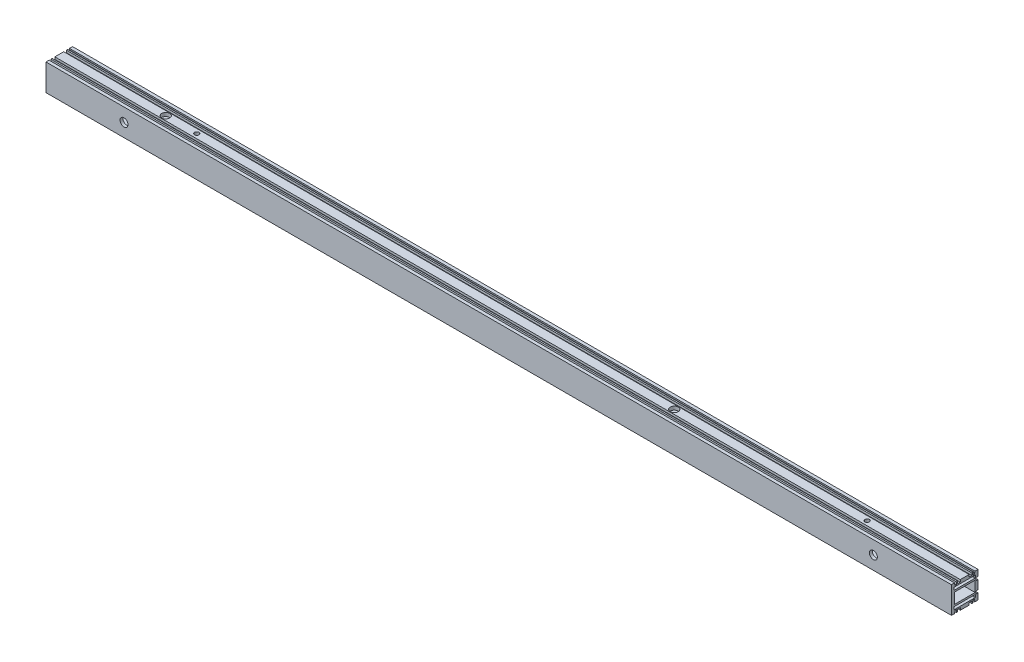
SolidWorks part; units mm, degrees
ref_plane "前视基准面" through (0, 0, 0) normal (0, 0, 1) x (1, 0, 0)
ref_plane "上视基准面" through (0, 0, 0) normal (0, 1, 0) x (1, 0, 0)
ref_plane "右视基准面" through (0, 0, 0) normal (1, 0, 0) x (0, 0, -1)
sketch "草图1" plane through (0, 0, 0) normal (1, 0, 0) x (0, 0, -1)
  line L0 (-15, 15) -> (15, -15) construction
  line L1 (-15, 15) -> (-11.5, 15)
  line L2 (-15, 15) -> (-15, -15)
  line L3 (-15, -15) -> (-11.5, -15)
  line L4 (15, 15) -> (15, 8)
  line L5 (15, 15) -> (-15, -15) construction
  line L6 (-11.5, 15) -> (-11.5, 13.5)
  line L7 (-11.5, 13.5) -> (-11, 13.5)
  line L8 (-11, 13.5) -> (-11, 12)
  line L9 (-11, 12) -> (-9.5, 12)
  line L10 (-9.5, 12) -> (-9.5, 15)
  line L11 (-9.5, 15) -> (-8, 15)
  line L12 (-8, 15) -> (-8, 12.5)
  line L13 (-8, 12.5) -> (-5, 12.5)
  line L14 (-5, 12.5) -> (-5, 15)
  line L15 (-5, 15) -> (5, 15)
  line L16 (0, 21.5201) -> (0, -18.309) construction
  line L17 (0, 55) -> (0, -55) construction
  line L18 (5, 12.5) -> (5, 15)
  line L19 (8, 12.5) -> (5, 12.5)
  line L20 (8, 15) -> (8, 12.5)
  line L21 (9.5, 15) -> (8, 15)
  line L22 (9.5, 12) -> (9.5, 15)
  line L23 (11, 12) -> (9.5, 12)
  line L24 (11, 13.5) -> (11, 12)
  line L25 (11.5, 13.5) -> (11, 13.5)
  line L26 (11.5, 15) -> (11.5, 13.5)
  line L27 (8, 15) -> (9.5, 15)
  line L28 (11.5, 15) -> (15, 15)
  line L29 (-19.8303, 0) -> (22.13, 0) construction
  line L30 (55, 0) -> (-55, 0) construction
  line L31 (8, -15) -> (9.5, -15)
  line L32 (11.5, -15) -> (11.5, -13.5)
  line L33 (11.5, -13.5) -> (11, -13.5)
  line L34 (11, -13.5) -> (11, -12)
  line L35 (11, -12) -> (9.5, -12)
  line L36 (9.5, -12) -> (9.5, -15)
  line L37 (9.5, -15) -> (8, -15)
  line L38 (8, -15) -> (8, -12.5)
  line L39 (8, -12.5) -> (5, -12.5)
  line L40 (5, -12.5) -> (5, -15)
  line L41 (-5, -15) -> (5, -15)
  line L42 (-5, -12.5) -> (-5, -15)
  line L43 (-8, -12.5) -> (-5, -12.5)
  line L44 (-8, -15) -> (-8, -12.5)
  line L45 (-9.5, -15) -> (-8, -15)
  line L46 (-9.5, -12) -> (-9.5, -15)
  line L47 (-11, -12) -> (-9.5, -12)
  line L48 (-11, -13.5) -> (-11, -12)
  line L49 (-11.5, -13.5) -> (-11, -13.5)
  line L50 (-11.5, -15) -> (-11.5, -13.5)
  line L51 (-9.5, -15) -> (-8, -15)
  line L52 (-5, -15) -> (5, -15)
  line L53 (8, -15) -> (9.5, -15)
  line L54 (11.5, -15) -> (15, -15)
  line L55 (15, 8) -> (12.5, 8)
  line L56 (12.5, 8) -> (12.5, 5)
  line L57 (12.5, 5) -> (15, 5)
  line L58 (12.5, -5) -> (15, -5)
  line L59 (12.5, -8) -> (12.5, -5)
  line L60 (15, -8) -> (12.5, -8)
  line L61 (15, 5) -> (15, -5)
  line L62 (15, -8) -> (15, -15)
  line L63 (12, -10.5) -> (12, -8.5)
  line L64 (-11.5, 11) -> (11.5, 11)
  line L65 (-12, 10.5) -> (-12, 8.5)
  line L66 (-11.5, 8) -> (11.5, 8)
  line L67 (12, 10.5) -> (12, 8.5)
  line L68 (-11.5, -8) -> (11.5, -8)
  line L69 (-12, -10.5) -> (-12, -8.5)
  line L70 (-11.5, -11) -> (11.5, -11)
  line L72 (-11.75, 6) -> (11.75, 6)
  line L73 (-11.75, 6) -> (-11.75, -6)
  line L74 (-11.75, -6) -> (11.75, -6)
  line L75 (11.75, 6) -> (11.75, -6)
  arc A0 (12, 8.5) -> (11.5, 8) centre (11.5, 8.5) cw
  arc A1 (11.5, 11) -> (12, 10.5) centre (11.5, 10.5) cw
  arc A2 (-11.5, 11) -> (-12, 10.5) centre (-11.5, 10.5) ccw
  arc A3 (-11.5, 8) -> (-12, 8.5) centre (-11.5, 8.5) cw
  arc A8 (-11.5, -8) -> (-12, -8.5) centre (-11.5, -8.5) ccw
  arc A9 (-11.5, -11) -> (-12, -10.5) centre (-11.5, -10.5) cw
  arc A10 (11.5, -11) -> (12, -10.5) centre (11.5, -10.5) ccw
  arc A11 (12, -8.5) -> (11.5, -8) centre (11.5, -8.5) ccw
  point P69 (12, 11)
  point P72 (-12, 11)
  point P77 (-11, -13.5)
  point P80 (11, -13.5)
  point P83 (11, 13.5)
  point P86 (-11, 13.5)
  point P99 (-12, -11)
  point P100 (12, -11)
  dimension "D17" = 0.5
  dimension "D1" = 3.5
  dimension "D2" = 1.5
  dimension "D3" = 0.5
  dimension "D4" = 1.5
  dimension "D5" = 3
  dimension "D6" = 30
  dimension "D7" = 30
  dimension "D8" = 1.5
  dimension "D9" = 2.5
  dimension "D10" = 3
  dimension "D11" = 2.5
  dimension "D12" = 7
  dimension "D13" = 3
  dimension "D14" = 4
  dimension "D15" = 3
  dimension "D16" = 24
  dimension "D19" = 23.5
  dimension "D20" = 12
extrude "凸台-拉伸1" add sketch "草图1" along normal mid plane 1021
hole_wizard "M6 螺纹孔1" positions "草图3" profile "草图2" tap size "M6" standard "GB"
sketch "草图3" plane through (0, 0, -15) normal (0, 0, -1) x (-1, 0, 0)
  point P0 (460.5, 0)
  point P3 (445.5, 0)
  point P6 (-445.5, 0)
  point P9 (-460.5, 0)
sketch "草图2" plane through (-460.5, 0, -15) normal (1, 0, 0) x (0, 1, 0)
  line L0 (0, 0) -> (0, 20.5022)
  line L1 (0, 20.5022) -> (2.5, 19)
  line L2 (2.5, 19) -> (2.5, 0)
  line L5 (2.5, 0) -> (0, 0)
  line L10 (0, 20.5022) -> (-2.5, 19) construction
  line L11 (0, -6.35) -> (0, 107.95) construction
  dimension "螺纹孔钻头直径" = 5
  dimension "螺纹孔钻头深度" = 19
  dimension "导头角度" = 118
cosmetic thread "孔螺蚊线1" parameters "D1"=3.25, "D2"=6
cosmetic thread "孔螺蚊线2" parameters "D1"=3.25, "D2"=6
cosmetic thread "孔螺蚊线3" parameters "D1"=3.25, "D2"=6
cosmetic thread "孔螺蚊线4" parameters "D1"=3.25, "D2"=6
hole_wizard "M6 螺纹孔2" positions "草图5" profile "草图4" tap size "M6" standard "GB"
sketch "草图5" plane through (0, -15, 0) normal (0, -1, 0) x (-1, 0, 0)
  point P0 (-460.5, 0)
  point P3 (-445.5, 0)
  point P6 (215.5, 0)
  point P9 (230.5, 0)
  point P12 (445.5, 0)
  point P15 (460.5, 0)
sketch "草图4" plane through (460.5, -15, 0) normal (1, 0, 0) x (0, 0, -1)
  line L0 (0, 0) -> (0, 16.5022)
  line L1 (0, 16.5022) -> (2.5, 15)
  line L2 (2.5, 15) -> (2.5, 0)
  line L5 (2.5, 0) -> (0, 0)
  line L10 (0, 16.5022) -> (-2.5, 15) construction
  line L11 (0, -6.35) -> (0, 107.95) construction
  dimension "螺纹孔钻头直径" = 5
  dimension "螺纹孔钻头深度" = 15
  dimension "导头角度" = 118
cosmetic thread "孔螺蚊线5" parameters "D1"=9, "D2"=6
cosmetic thread "孔螺蚊线6" parameters "D1"=9, "D2"=6
cosmetic thread "孔螺蚊线7" parameters "D1"=9, "D2"=6
cosmetic thread "孔螺蚊线8" parameters "D1"=9, "D2"=6
cosmetic thread "孔螺蚊线9" parameters "D1"=9, "D2"=6
cosmetic thread "孔螺蚊线10" parameters "D1"=9, "D2"=6
hole_wizard "Ø9.0 (9) 直径孔1" positions "草图7" profile "草图8" hole size "Ø9.0" standard "GB" end condition through all
sketch "草图7" plane through (0, 0, 15) normal (0, 0, 1) x (1, 0, 0)
  line L0 (510.5, 15) -> (-510.5, 15) construction
  line L1 (510.5, 15) -> (510.5, -15) construction
  line L2 (-510.5, 15) -> (-510.5, -15) construction
  point P0 (-422.5, 0)
  point P2 (422.5, 0)
  dimension "D1" = 15
  dimension "D2" = 88
  dimension "D3" = 15
  dimension "D4" = 88
sketch "草图8" plane through (-422.5, 0, 15) normal (1, 0, 0) x (0, -1, 0)
  line L0 (0, 0) -> (0, 30)
  line L1 (0, 30) -> (4.5, 30)
  line L2 (4.5, 30) -> (4.5, 0)
  line L5 (4.5, 0) -> (0, 0)
  line L11 (0, -6.35) -> (0, 107.95) construction
  dimension "通孔孔直径" = 9
  dimension "通孔孔深度" = 30
hole_wizard "M6 螺纹孔3" positions "草图10" profile "草图9" tap size "M6" standard "GB"
sketch "草图10" plane through (0, 15, 0) normal (0, 1, 0) x (1, 0, 0)
  line L0 (510.5, 15) -> (-510.5, 15) construction
  line L1 (510.5, -5) -> (510.5, 5) construction
  line L2 (-510.5, -5) -> (-510.5, 5) construction
  point P0 (-355.5, 0)
  point P2 (400.5, 0)
  dimension "D1" = 15
  dimension "D2" = 110
  dimension "D3" = 15
  dimension "D4" = 155
sketch "草图9" plane through (-355.5, 15, 0) normal (1, 0, 0) x (0, 0, 1)
  line L0 (0, 0) -> (0, 16.5022)
  line L1 (0, 16.5022) -> (2.5, 15)
  line L2 (2.5, 15) -> (2.5, 0)
  line L5 (2.5, 0) -> (0, 0)
  line L10 (0, 16.5022) -> (-2.5, 15) construction
  line L11 (0, -6.35) -> (0, 107.95) construction
  dimension "螺纹孔钻头直径" = 5
  dimension "螺纹孔钻头深度" = 15
  dimension "导头角度" = 118
cosmetic thread "孔螺蚊线11" parameters "D1"=9, "D2"=6
cosmetic thread "孔螺蚊线12" parameters "D1"=9, "D2"=6
hole_wizard "Ø9.0 (9) 直径孔2" positions "草图12" profile "草图11" hole size "Ø9.0" standard "GB" end condition through all
sketch "草图12" plane through (0, -15, 0) normal (0, -1, 0) x (-1, 0, 0)
  line L0 (-510.5, 15) -> (510.5, 15) construction
  line L1 (510.5, -5) -> (510.5, 5) construction
  line L2 (-510.5, -5) -> (-510.5, 5) construction
  point P0 (-183, 0)
  point P2 (390.5, 0)
  dimension "D1" = 15
  dimension "D2" = 120
  dimension "D3" = 15
  dimension "D4" = 327.5
sketch "草图11" plane through (183, -15, 0) normal (1, 0, 0) x (0, 0, -1)
  line L0 (0, 0) -> (0, 30)
  line L1 (0, 30) -> (4.5, 30)
  line L2 (4.5, 30) -> (4.5, 0)
  line L5 (4.5, 0) -> (0, 0)
  line L11 (0, -6.35) -> (0, 107.95) construction
  dimension "通孔孔直径" = 9
  dimension "通孔孔深度" = 30
hole_wizard "Ø7.0 (7) 直径孔1" positions "草图14" profile "草图13" hole size "Ø7.0" standard "GB"
sketch "草图14" plane through (0, -15, 0) normal (0, -1, 0) x (-1, 0, 0)
  line L1 (-510.5, 15) -> (510.5, 15) construction
  line L2 (510.5, -5) -> (510.5, 5) construction
  line L3 (-510.5, -5) -> (-510.5, 5) construction
  point P0 (-400.5, 0)
  point P2 (355.5, 0)
  dimension "D1" = 15
  dimension "D2" = 155
  dimension "D3" = 15
  dimension "D4" = 110
sketch "草图13" plane through (400.5, -15, 0) normal (1, 0, 0) x (0, 0, -1)
  line L0 (0, 0) -> (0, 17.103)
  line L1 (0, 17.103) -> (3.5, 15)
  line L2 (3.5, 15) -> (3.5, 0)
  line L5 (3.5, 0) -> (0, 0)
  line L10 (0, 17.103) -> (-3.5, 15) construction
  line L11 (0, -6.35) -> (0, 107.95) construction
  dimension "孔直径" = 7
  dimension "孔深度" = 15
  dimension "导头角度" = 118
hole_wizard "M6 螺纹孔4" positions "草图16" profile "草图15" tap size "M6" standard "GB"
sketch "草图16" plane through (0, 0, -15) normal (0, 0, -1) x (-1, 0, 0)
  line L0 (-510.5, 15) -> (510.5, 15) construction
  line L1 (-510.5, 5) -> (-510.5, -5) construction
  point P0 (-368.5, 0)
  point P2 (-298.5, 0)
  dimension "D1" = 15
  dimension "D2" = 142
  dimension "D3" = 70
  dimension "D4" = 15
sketch "草图15" plane through (368.5, 0, -15) normal (1, 0, 0) x (0, 1, 0)
  line L0 (0, 0) -> (0, 18.5022)
  line L1 (0, 18.5022) -> (2.5, 17)
  line L2 (2.5, 17) -> (2.5, 0)
  line L5 (2.5, 0) -> (0, 0)
  line L10 (0, 18.5022) -> (-2.5, 17) construction
  line L11 (0, -6.35) -> (0, 107.95) construction
  dimension "螺纹孔钻头直径" = 5
  dimension "螺纹孔钻头深度" = 17
  dimension "导头角度" = 118
cosmetic thread "孔螺蚊线13" parameters "D1"=3.25, "D2"=6
cosmetic thread "孔螺蚊线14" parameters "D1"=3.25, "D2"=6
